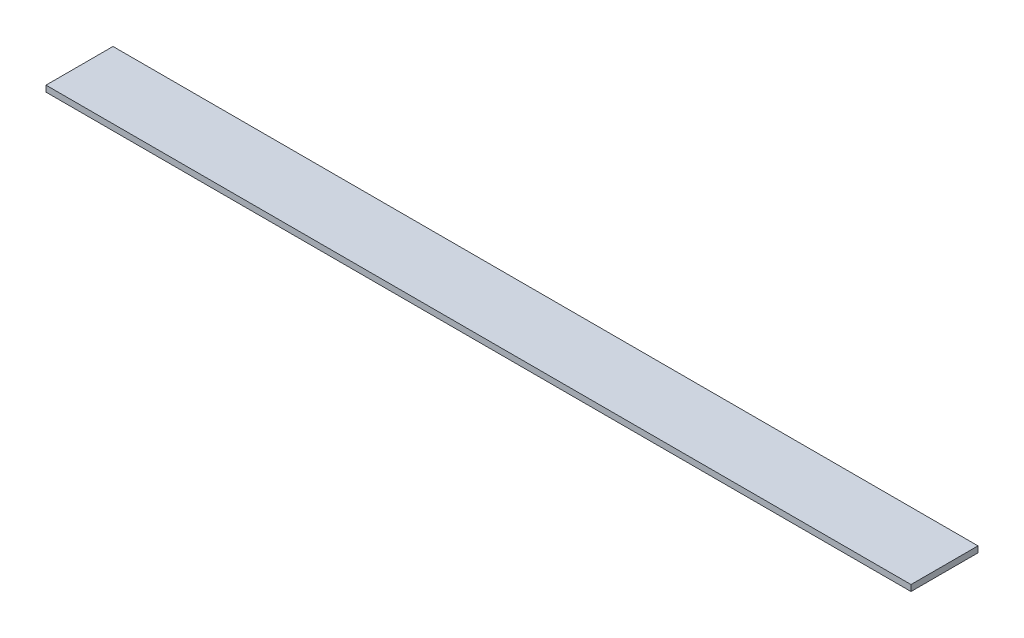
SolidWorks part; units mm, degrees
ref_plane "Front Plane" through (0, 0, 0) normal (0, 0, 1) x (1, 0, 0)
ref_plane "Top Plane" through (0, 0, 0) normal (0, 1, 0) x (1, 0, 0)
ref_plane "Right Plane" through (0, 0, 0) normal (1, 0, 0) x (0, 0, -1)
sketch "Sketch1" plane through (0, 0, 0) normal (0, 1, 0) x (1, 0, 0)
  line L1 (0, 0) -> (450.85, 0)
  line L2 (0, 0) -> (0, 34.925)
  line L3 (0, 34.925) -> (450.85, 34.925)
  line L4 (450.85, 0) -> (450.85, 34.925)
  dimension "D1" = 450.85
  dimension "D2" = 34.925
extrude "Boss-Extrude1" add sketch "Sketch1" along normal blind 3.175
